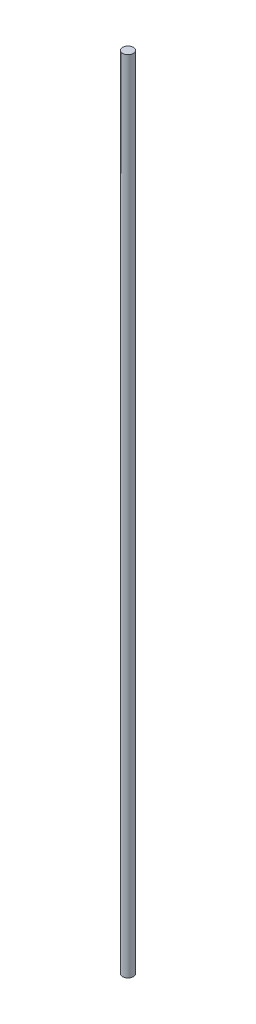
SolidWorks part; units mm, degrees
material "AISI 316 Annealed Stainless Steel Bar (SS)"
ref_plane "Front Plane" through (0, 0, 0) normal (0, 0, 1) x (1, 0, 0)
ref_plane "Top Plane" through (0, 0, 0) normal (0, 1, 0) x (1, 0, 0)
ref_plane "Right Plane" through (0, 0, 0) normal (1, 0, 0) x (0, 0, -1)
sketch "Sketch1" plane through (0, 0, 0) normal (0, 1, 0) x (1, 0, 0)
  circle A0 centre (0, 0) radius 4
  dimension "D1" = 8
extrude "Boss-Extrude1" add sketch "Sketch1" along normal mid plane 600
